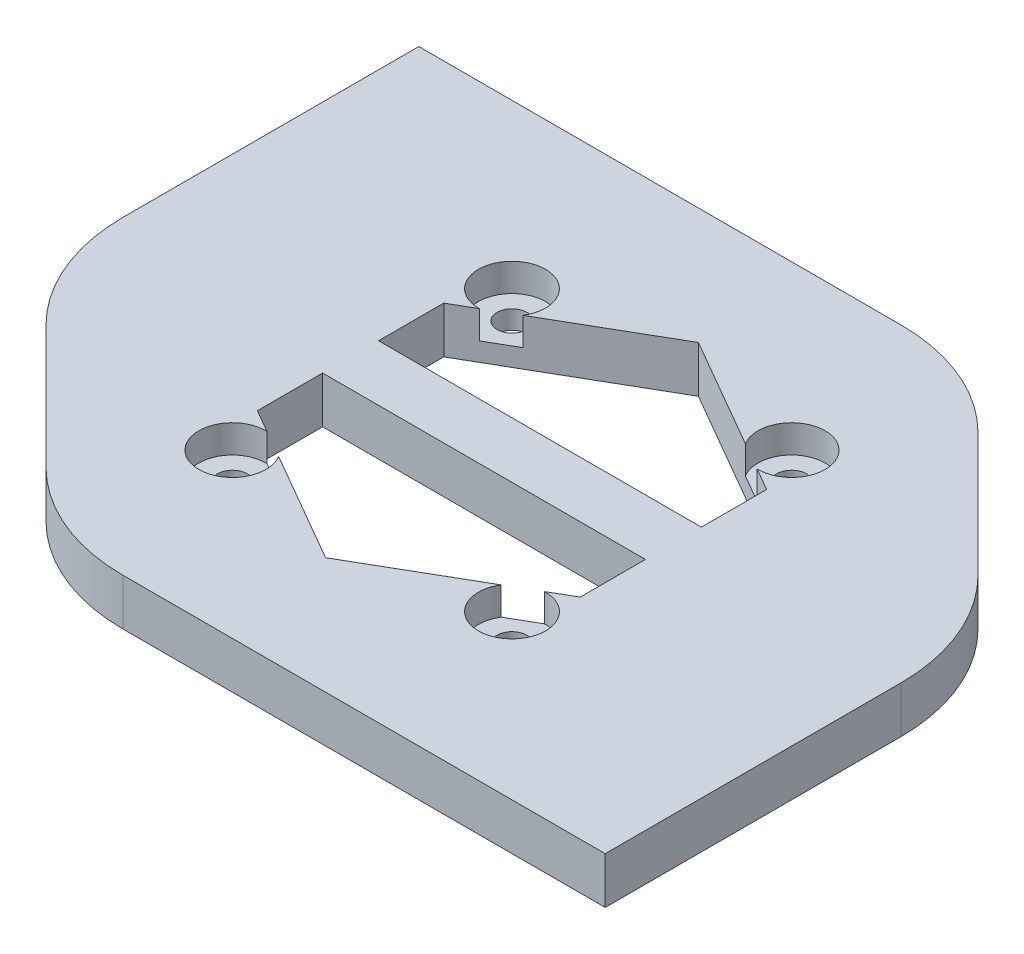
SolidWorks part; units mm, degrees
ref_plane "Front Plane" through (0, 0, 0) normal (0, 0, 1) x (1, 0, 0)
ref_plane "Top Plane" through (0, 0, 0) normal (0, 1, 0) x (1, 0, 0)
ref_plane "Right Plane" through (0, 0, 0) normal (1, 0, 0) x (0, 0, -1)
sketch "Sketch1" plane through (0, 0, 0) normal (0, 1, 0) x (1, 0, 0)
  line L1 (-42.5, -32.5) -> (42.5, -32.5)
  line L2 (-42.5, -32.5) -> (-42.5, 32.5)
  line L3 (-42.5, 32.5) -> (42.5, 32.5)
  line L4 (42.5, -32.5) -> (42.5, 32.5)
  line L5 (-42.5, -32.5) -> (42.5, 32.5) construction
  line L6 (-42.5, 32.5) -> (42.5, -32.5) construction
  point P0 (0, 0)
  dimension "D1" = 85
  dimension "D2" = 65
extrude "Boss-Extrude1" add sketch "Sketch1" along normal blind 5
sketch "Sketch3" plane through (0, 5, 0) normal (0, 1, 0) x (1, 0, 0)
  line L1 (-15, -15) -> (15, -15)
  line L2 (-15, -15) -> (-15, 15)
  line L3 (-15, 15) -> (15, 15)
  line L4 (15, -15) -> (15, 15)
  line L5 (-15, -15) -> (15, 15) construction
  line L6 (-15, 15) -> (15, -15) construction
  circle A0 centre (-15, 15) radius 1.6
  circle A1 centre (15, 15) radius 1.6
  circle A2 centre (15, -15) radius 1.6
  circle A3 centre (-15, -15) radius 1.6
  point P0 (0, 0)
  dimension "D3" = 3.2
  dimension "D1" = 30
  dimension "D2" = 30
extrude "Cut-Extrude1" cut sketch "Sketch3" against normal blind 46 contours L3 A0 L2 | L2 A0 L3 | L3 A1 L4 | L4 A1 L3 | L2 A3 L1 | L1 A3 L2 | L4 A2 L1 | L1 A2 L4
sketch "Sketch4" plane through (0, 5, 0) normal (0, 1, 0) x (1, 0, 0)
  line L1 (0, -20) -> (17.3205, -10)
  line L2 (17.3205, -10) -> (17.3205, 10)
  line L3 (17.3205, 10) -> (0, 20)
  line L4 (0, 20) -> (-17.3205, 10)
  line L5 (-17.3205, 10) -> (-17.3205, -10)
  line L6 (-17.3205, -10) -> (0, -20)
  circle A0 centre (0, 0) radius 17.3205 construction
  dimension "D1" = 20
extrude "Cut-Extrude2" cut sketch "Sketch4" against normal blind 46
sketch "Sketch5" plane through (0, 5, 0) normal (0, 1, 0) x (1, 0, 0)
  line L1 (-22.8414, 3) -> (22.8414, 3)
  line L2 (-22.8414, 3) -> (-22.8414, -3)
  line L3 (-22.8414, -3) -> (22.8414, -3)
  line L4 (22.8414, 3) -> (22.8414, -3)
  line L5 (-22.8414, 3) -> (22.8414, -3) construction
  line L6 (-22.8414, -3) -> (22.8414, 3) construction
  point P0 (0, 0)
  dimension "D1" = 6
extrude "Boss-Extrude3" add sketch "Sketch5" against normal up to surface (5 mm away) up to face at (0, 0, 0)
sketch "Sketch6" plane through (0, 5, 0) normal (0, 1, 0) x (1, 0, 0)
  circle A2 centre (-15, 15) radius 3.6
  circle A3 centre (-15, 15) radius 3.6
  circle A4 centre (15, 15) radius 3.6
  circle A5 centre (15, 15) radius 3.6
  circle A7 centre (-15, -15) radius 3.6
  circle A8 centre (-15, -15) radius 3.6
  circle A10 centre (15, -15) radius 3.6
  circle A11 centre (15, -15) radius 3.6
  dimension "D1" = 2
  dimension "D2" = 2
  dimension "D3" = 2
  dimension "D4" = 2
extrude "Cut-Extrude3" cut sketch "Sketch6" against normal blind 3 contours A3 | A5 | A8 | A11
sketch "Sketch7" plane through (0, 5, 0) normal (0, 1, 0) x (1, 0, 0)
  line L0 (-17.5, -32.5) -> (-42.5, -7.5)
  line L1 (-42.5, -32.5) -> (42.5, -32.5) construction
  line L2 (-42.5, 32.5) -> (-42.5, -32.5) construction
  line L3 (42.5, 7.5) -> (17.5, 32.5)
  line L4 (42.5, -32.5) -> (42.5, 32.5) construction
  line L5 (42.5, 32.5) -> (-42.5, 32.5) construction
  line L7 (-42.5, 32.5) -> (42.5, 32.5)
  line L8 (-42.5, 32.5) -> (-42.5, -32.5)
  line L9 (-42.5, -32.5) -> (42.5, -32.5)
  line L10 (42.5, 32.5) -> (42.5, -32.5)
  line L11 (-42.5, 32.5) -> (42.5, -32.5) construction
  line L12 (-42.5, -32.5) -> (42.5, 32.5) construction
  point P13 (0, 0)
  line M19 (42.5, -32.5) -> (42.5, 32.5)
  line M20 (42.5, 32.5) -> (-42.5, 32.5)
  line M21 (-42.5, 32.5) -> (-42.5, -32.5)
  line M22 (-42.5, -32.5) -> (42.5, -32.5)
  dimension "D1" = 25
  dimension "D2" = 25
  dimension "D3" = 25
  dimension "D4" = 25
extrude "Cut-Extrude4" cut sketch "Sketch7" against normal mid plane 10 contours L3 M19 M20 | L0 M22 M21
fillet "Fillet1" radius 20 4 edges at (-42.5, 2.5, 7.5) (-17.5, 2.5, 32.5) (42.5, 2.5, -7.5) (17.5, 2.5, -32.5)
